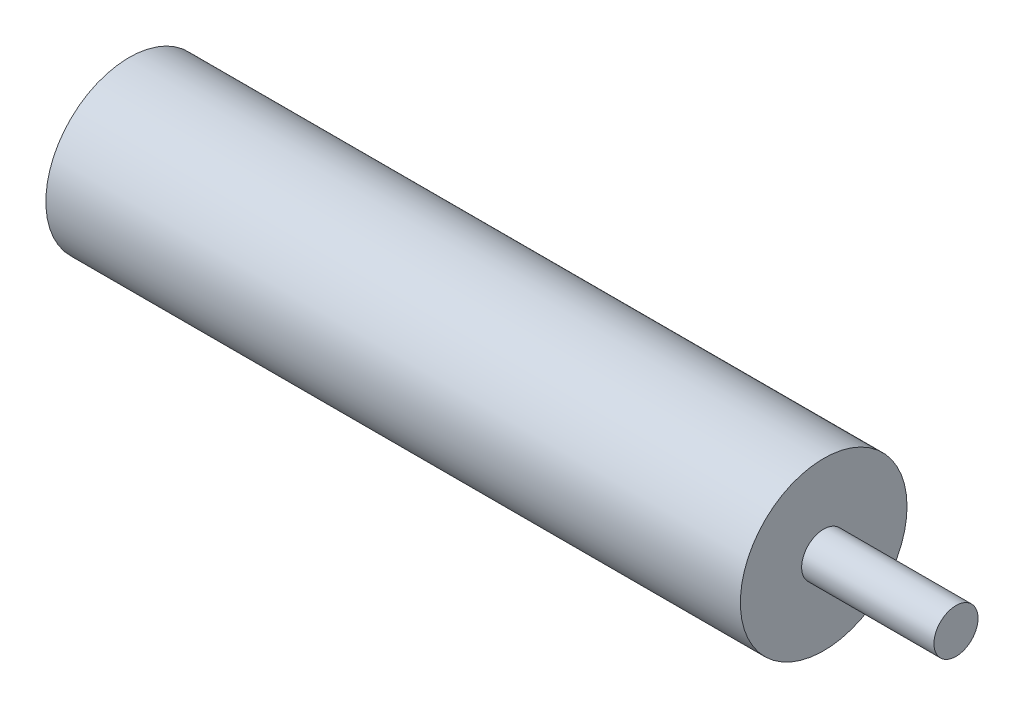
SolidWorks part; units mm, degrees
ref_plane "Front Plane" through (0, 0, 0) normal (0, 0, 1) x (1, 0, 0)
ref_plane "Top Plane" through (0, 0, 0) normal (0, 1, 0) x (1, 0, 0)
ref_plane "Right Plane" through (0, 0, 0) normal (1, 0, 0) x (0, 0, -1)
sketch "Sketch1" plane through (0, 0, 0) normal (1, 0, 0) x (0, 0, -1)
  circle A0 centre (0, 0) radius 6
  dimension "D1" = 12
extrude "Boss-Extrude1" add sketch "Sketch1" along normal blind 50
sketch "Sketch2" plane through (50, 0, 0) normal (1, 0, 0) x (0, 0, -1)
  circle A0 centre (0, 0) radius 1.5875
extrude "Boss-Extrude2" add sketch "Sketch2" along normal blind 9.525
